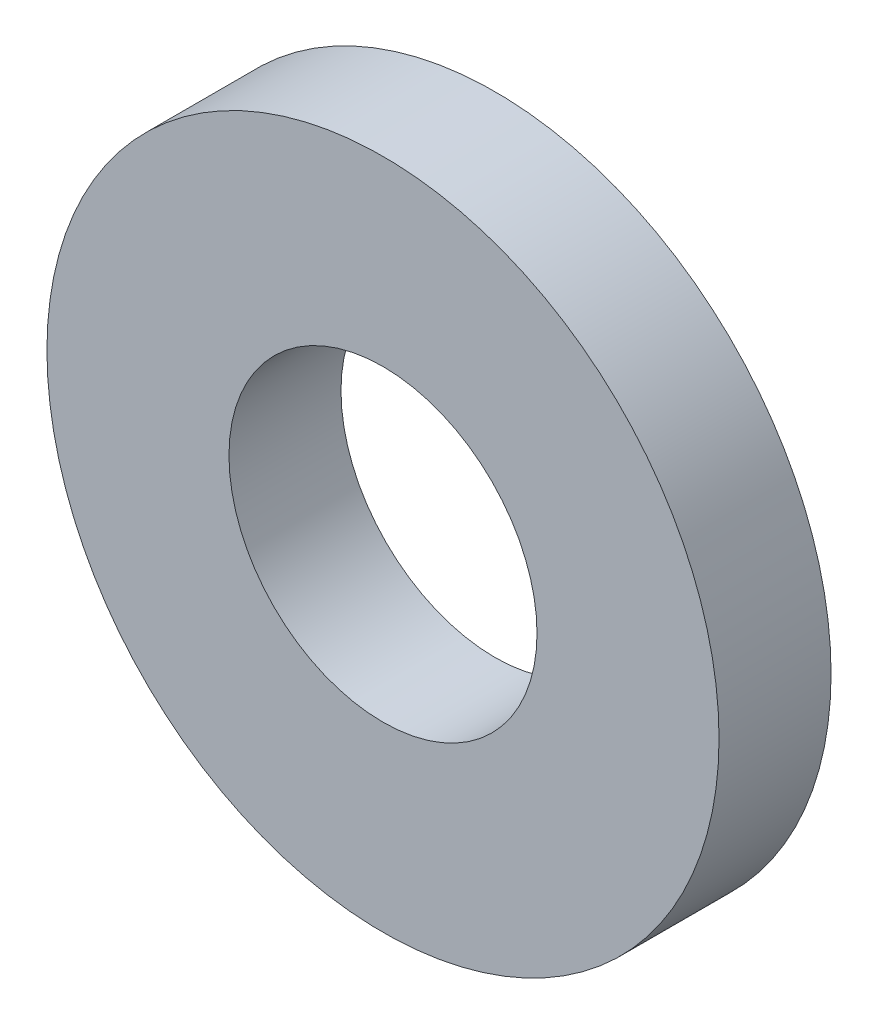
SolidWorks part; units mm, degrees
ref_plane "Спереди" through (0, 0, 0) normal (0, 0, 1) x (1, 0, 0)
ref_plane "Сверху" through (0, 0, 0) normal (0, 1, 0) x (1, 0, 0)
ref_plane "Справа" through (0, 0, 0) normal (1, 0, 0) x (0, 0, -1)
sketch "Эскиз1" plane through (0, 0, 0) normal (0, 0, 1) x (1, 0, 0)
  circle A0 centre (0, 0) radius 2.75
  circle A1 centre (0, 0) radius 6
  dimension "D1" = 5.5
  dimension "D2" = 12
extrude "Бобышка-Вытянуть1" add sketch "Эскиз1" along normal blind 2
